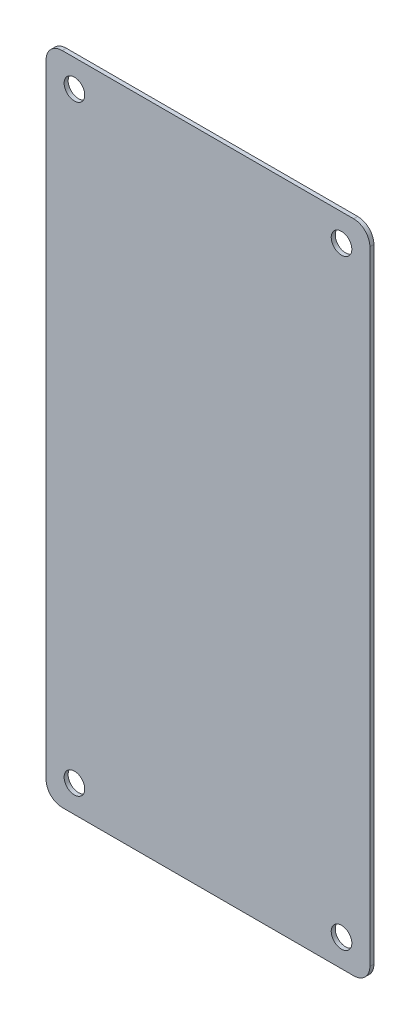
SolidWorks part; units mm, degrees
material "AISI 304"
ref_plane "Front Plane" through (0, 0, 0) normal (0, 0, 1) x (1, 0, 0)
ref_plane "Top Plane" through (0, 0, 0) normal (0, 1, 0) x (1, 0, 0)
ref_plane "Right Plane" through (0, 0, 0) normal (1, 0, 0) x (0, 0, -1)
sketch "Sketch1" plane through (0, 0, 0) normal (0, 0, 1) x (1, 0, 0)
  line L1 (-40, -81) -> (40, -81)
  line L2 (-40, -81) -> (-40, 81)
  line L3 (-40, 81) -> (40, 81)
  line L4 (40, -81) -> (40, 81)
  line L5 (-40, -81) -> (40, 81) construction
  line L6 (-40, 81) -> (40, -81) construction
  point P0 (0, 0)
  dimension "D1" = 80
  dimension "D2" = 162
extrude "Boss-Extrude1" add sketch "Sketch1" along normal blind 1
fillet "Fillet1" radius 4 4 edges at (-40, 81, 0.5) (-40, -81, 0.5) (40, -81, 0.5) (40, 81, 0.5)
sketch "Sketch2" plane through (0, 0, 0) normal (0, 0, -1) x (-1, 0, 0)
  circle A0 centre (-33, -74.25) radius 2.55
  circle A3 centre (-33, 74.25) radius 2.55
  circle A4 centre (33, 74.25) radius 2.55
  circle A5 centre (33, -74.25) radius 2.55
  dimension "D1" = 5.1
extrude "Cut-Extrude1" cut sketch "Sketch2" against normal through all
equation "\"Base-Width\"= 420"
equation "\"Base-Height\"= 320"
equation "\"Support-Rod-Diameter\"= 16"
equation "\"Support-Rod-X-Offset\"= 35"
equation "\"Support-Rod-Y-Offset\"= 35"
equation "\"Base-Thickness\"= 5"
equation "\"Base-Depth\"= 82"
equation "\"Corner-Radius-Major\"= \"Support-Rod-Diameter\""
equation "\"Cutout-Horizontal\"= \"Base-Width\" * 0.8"
equation "\"Cutout-Vertical\"= \"Base-Height\" * 0.6"
equation "\"Outer-Support-Bore-Diameter\"= 6.1"
equation "\"Inner-Support-Bore-Diameter\"= 8.2"
equation "\"Cutout-Depth\"= 20"
equation "\"D1@Sketch1\"=\"Base-Depth\" - 2"
equation "\"D2@Sketch1\"=(\"Base-Width\" - (\"Support-Rod-Diameter\" * 6))/2"
equation "\"D2@Sketch1\"=\"Base-Width\""
equation "\"D1@Sketch7\"=\"Cutout-Vertical\""
equation "\"D2@Sketch6\"=\"Cutout-Horizontal\""
equation "\"D2@Sketch8\"= \"Base-Width\" - ( \"Support-Rod-X-Offset\" ) + 5"
equation "\"D1@Sketch8\" = \"Base-Height\" - \"Support-Rod-Y-Offset\" + 10"
equation "\"D1@Major-Fillet\" = \"Corner-Radius-Major\""
equation "\"D1@Sketch1\"=\"Base-Height\""
